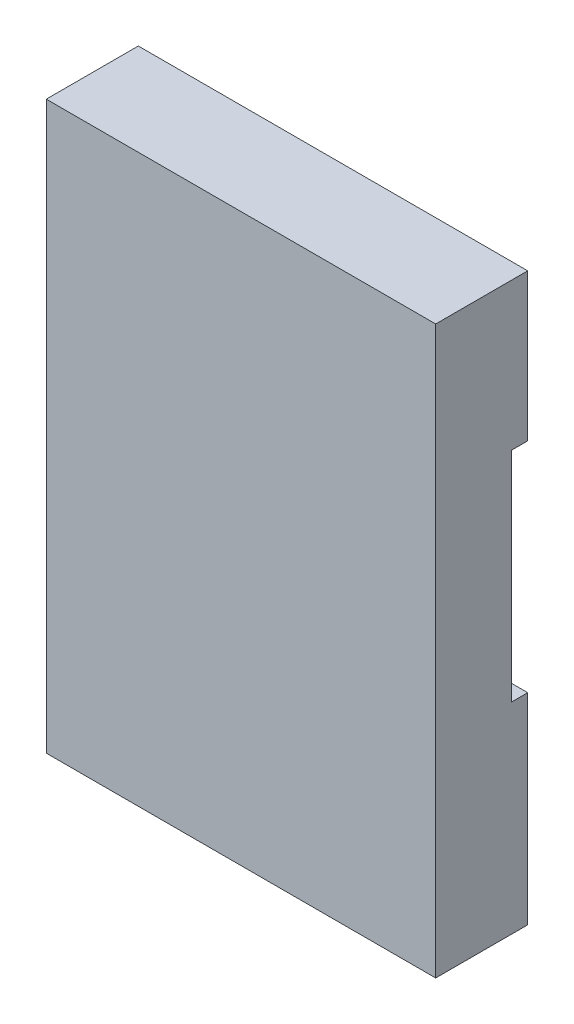
SolidWorks part; units mm, degrees
ref_plane "Front Plane" through (0, 0, 0) normal (0, 0, 1) x (1, 0, 0)
ref_plane "Top Plane" through (0, 0, 0) normal (0, 1, 0) x (1, 0, 0)
ref_plane "Right Plane" through (0, 0, 0) normal (1, 0, 0) x (0, 0, -1)
sketch "Sketch1" plane through (0, 0, 0) normal (0, 0, 1) x (1, 0, 0)
  line L1 (-13.75, 20) -> (13.75, 20)
  line L2 (-13.75, 20) -> (-13.75, -20)
  line L3 (-13.75, -20) -> (13.75, -20)
  line L4 (13.75, 20) -> (13.75, -20)
  line L5 (-13.75, 20) -> (13.75, -20) construction
  line L6 (-13.75, -20) -> (13.75, 20) construction
  point P0 (0, 0)
  dimension "D1" = 40
  dimension "D2" = 27.5
extrude "Boss-Extrude1" add sketch "Sketch1" along normal blind 6.5
sketch "Sketch2" plane through (0, 0, 0) normal (0, 0, -1) x (-1, 0, 0)
  line L0 (-13.75, -20) -> (-13.75, 20) construction
  line L1 (-13.75, 9.6) -> (3.5, 9.6)
  line L2 (-13.75, 9.6) -> (-13.75, -5.8)
  line L3 (-13.75, -5.8) -> (3.5, -5.8)
  line L4 (3.5, 9.6) -> (3.5, -5.8)
  line L5 (-13.75, 20) -> (13.75, 20) construction
  dimension "D1" = 10.4
  dimension "D2" = 15.4
  dimension "D3" = 17.25
extrude "Cut-Extrude1" cut sketch "Sketch2" against normal blind 1.15
sketch "Sketch3" plane through (0, 0, 0) normal (0, 0, -1) x (-1, 0, 0)
  line L0 (13.75, -20) -> (-13.75, -20) construction
  line L1 (-7.4364, -20) -> (7.8758, -20)
  line L2 (-7.4364, -20) -> (-7.4364, -17.75)
  line L3 (-7.4364, -17.75) -> (7.8758, -17.75)
  line L4 (7.8758, -20) -> (7.8758, -17.75)
  dimension "D1" = 2.25
extrude "Cut-Extrude2" cut sketch "Sketch3" against normal blind 1.15
